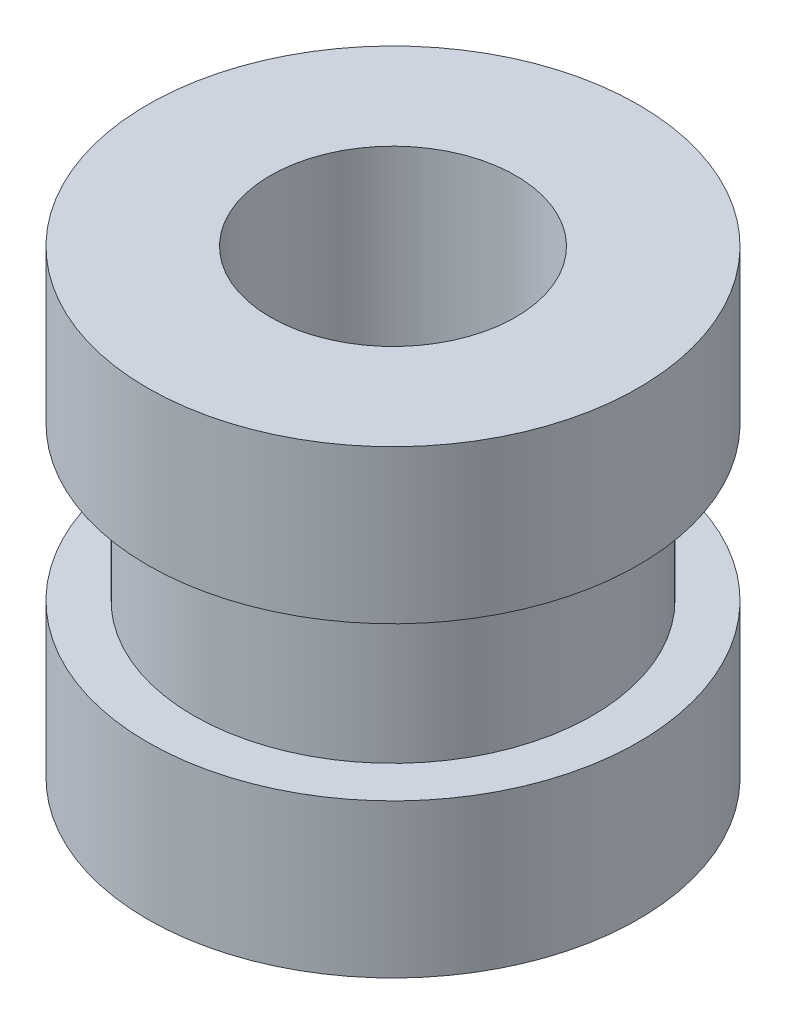
SolidWorks part; units mm, degrees
material "H62"
ref_plane "前视基准面" through (0, 0, 0) normal (0, 0, 1) x (1, 0, 0)
ref_plane "上视基准面" through (0, 0, 0) normal (0, 1, 0) x (1, 0, 0)
ref_plane "右视基准面" through (0, 0, 0) normal (1, 0, 0) x (0, 0, -1)
other "Configuration Table"
sketch "草图1" plane through (0, 0, 0) normal (0, 1, 0) x (1, 0, 0)
  circle A0 centre (0, 0) radius 1.6
  dimension "D1" = 3.2
extrude "凸台-拉伸1" add sketch "草图1" along normal blind 1
sketch "草图2" plane through (0, 1, 0) normal (0, 1, 0) x (1, 0, 0)
  circle A0 centre (0, 0) radius 1.3
  circle A1 centre (0, 0) radius 1.6 construction
  dimension "D1" = 0.3
extrude "凸台-拉伸2" add sketch "草图2" along normal blind 1
sketch "草图3" plane through (0, 2, 0) normal (0, 1, 0) x (1, 0, 0)
  circle A1 centre (0, 0) radius 1.6
  circle A2 centre (0, 0) radius 1.6
  dimension "D1" = 0
extrude "凸台-拉伸3" add sketch "草图3" along normal blind 1
hole_wizard "M2 螺纹孔1" positions "草图4" profile "草图5" tap size "M2" standard "GB" end condition through all
sketch "草图4" plane through (0, 3, 0) normal (0, 1, 0) x (1, 0, 0)
  point P0 (0, 0)
sketch "草图5" plane through (0, 3, 0) normal (1, 0, 0) x (0, 0, 1)
  line L0 (0, 0) -> (0, 3)
  line L1 (0, 3) -> (0.8, 3)
  line L2 (0.8, 3) -> (0.8, 0)
  line L5 (0.8, 0) -> (0, 0)
  line L11 (0, -6.35) -> (0, 107.95) construction
  dimension "通孔螺纹孔钻头直径" = 1.6
  dimension "通孔螺纹孔钻头深度" = 3
cosmetic thread "孔螺蚊线1"
